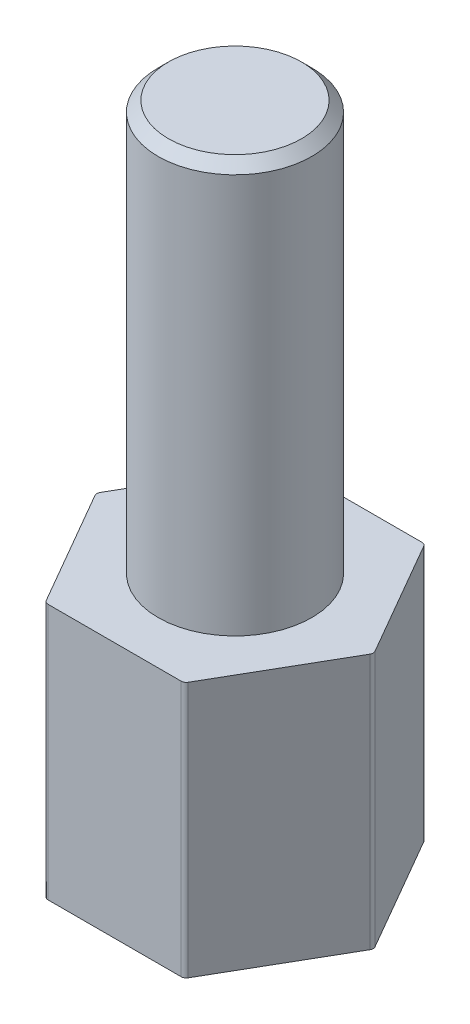
SolidWorks part; units mm, degrees
material "黄铜"
ref_plane "前视基准面" through (0, 0, 0) normal (0, 0, 1) x (1, 0, 0)
ref_plane "上视基准面" through (0, 0, 0) normal (0, 1, 0) x (1, 0, 0)
ref_plane "右视基准面" through (0, 0, 0) normal (1, 0, 0) x (0, 0, -1)
sketch "草图1" plane through (0, 0, 0) normal (0, 1, 0) x (1, 0, 0)
  line L1 (2.7135, 0) -> (1.3568, 2.35)
  line L2 (1.3568, 2.35) -> (-1.3568, 2.35)
  line L3 (-1.3568, 2.35) -> (-2.7135, 0)
  line L4 (-2.7135, 0) -> (-1.3568, -2.35)
  line L5 (-1.3568, -2.35) -> (1.3568, -2.35)
  line L6 (1.3568, -2.35) -> (2.7135, 0)
  circle A0 centre (0, 0) radius 2.35 construction
  dimension "D1" = 4.7
extrude "凸台-拉伸1" add sketch "草图1" along normal blind 5
sketch "草图2" plane through (0, 5, 0) normal (0, 1, 0) x (1, 0, 0)
  circle A0 centre (0, 0) radius 1.5
  dimension "D1" = 3
extrude "凸台-拉伸2" add sketch "草图2" along normal blind 8
cosmetic thread "装饰螺纹线1" parameters "D2"=2.459
sketch "草图3" plane through (0, 0, 0) normal (0, -1, 0) x (1, 0, 0)
  circle A0 centre (0, 0) radius 1.5
  dimension "D1" = 3
extrude "切除-拉伸1" cut sketch "草图3" against normal blind 4
cosmetic thread "装饰螺纹线2" parameters "D2"=4
chamfer "倒角1" distance 0.2 angle 45 2 edges at (0, 4, -1.5) (0, 13, 1.5)
fillet "圆角1" radius 0.1 6 edges at (1.3568, 2.5, 2.35) (-1.3568, 2.5, 2.35) (-2.7135, 2.5, 0) (-1.3568, 2.5, -2.35) (1.3568, 2.5, -2.35) (2.7135, 2.5, 0)
